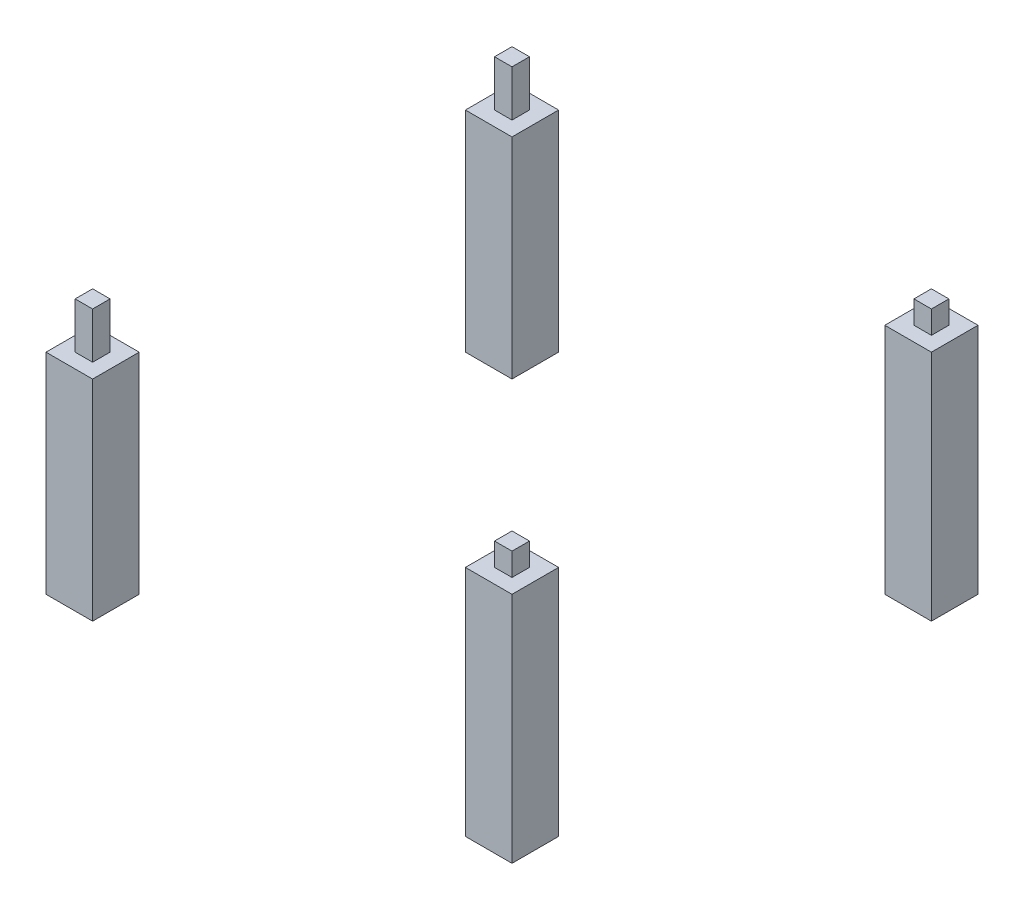
SolidWorks part; units mm, degrees
ref_plane "Front Plane" through (0, 0, 0) normal (0, 0, 1) x (1, 0, 0)
ref_plane "Top Plane" through (0, 0, 0) normal (0, 1, 0) x (1, 0, 0)
ref_plane "Right Plane" through (0, 0, 0) normal (1, 0, 0) x (0, 0, -1)
sketch "Croquis2" plane through (0, 0, 0) normal (0, 1, 0) x (1, 0, 0)
  line L1 (-90, -90) -> (90, -90) construction
  line L2 (-90, -90) -> (-90, 90) construction
  line L3 (-90, 90) -> (90, 90) construction
  line L4 (90, -90) -> (90, 90) construction
  line L5 (-90, -90) -> (90, 90) construction
  line L6 (-90, 90) -> (90, -90) construction
  line L11 (-86, -94) -> (-94, -86) construction
  line L12 (-86, -86) -> (-94, -94) construction
  line L13 (-100, -100) -> (-80, -100)
  line L14 (-100, -100) -> (-100, -80)
  line L15 (-100, -80) -> (-80, -80)
  line L16 (-80, -100) -> (-80, -80)
  line L17 (-100, -100) -> (-80, -80) construction
  line L18 (-100, -80) -> (-80, -100) construction
  line L19 (80, -100) -> (100, -100)
  line L20 (80, -100) -> (100, -80) construction
  line L21 (80, -80) -> (100, -100) construction
  line L22 (80, -80) -> (100, -80)
  line L24 (100, -100) -> (100, -80)
  line L29 (80, -100) -> (80, -80)
  line L33 (-100, 80) -> (-100, 100)
  line L35 (-80, 80) -> (-80, 100)
  line L36 (-100, 80) -> (-80, 100) construction
  line L37 (-100, 100) -> (-80, 80) construction
  line L40 (-100, 80) -> (-80, 80)
  line L41 (-100, 100) -> (-80, 100)
  line L43 (80, 100) -> (100, 80) construction
  line L44 (100, 80) -> (100, 100)
  line L45 (80, 80) -> (80, 100)
  line L48 (80, 80) -> (100, 100) construction
  line L49 (80, 100) -> (100, 100)
  line L51 (80, 80) -> (100, 80)
  point P0 (0, 0)
  point P14 (0, 0)
  point P38 (0, 0)
  point P39 (0, 0)
  point P40 (0, 0)
  dimension "D1" = 180
  dimension "D2" = 180
  dimension "D3" = 20
extrude "Saliente-Extruir3" add sketch "Croquis2" along normal blind 90 contours L13 L16 L15 L14 | L35 L41 L33 L40
sketch "Croquis5" plane through (0, 0, 0) normal (0, 1, 0) x (1, 0, 0)
  line L1 (80, -100) -> (100, -100)
  line L2 (80, -100) -> (80, -80)
  line L3 (80, -80) -> (100, -80)
  line L4 (100, -100) -> (100, -80)
  line L5 (80, -100) -> (100, -80) construction
  line L6 (80, -80) -> (100, -100) construction
  line L7 (80, 80) -> (100, 80)
  line L8 (80, 80) -> (80, 100)
  line L9 (80, 100) -> (100, 100)
  line L10 (100, 80) -> (100, 100)
  line L11 (80, 80) -> (100, 100) construction
  line L12 (80, 100) -> (100, 80) construction
  point P1 (90, -90)
  point P7 (90, 90)
extrude "Saliente-Extruir4" add sketch "Croquis5" along normal blind 100 separate body
sketch "Croquis6" plane through (0, 100, 0) normal (0, 1, 0) x (1, 0, 0)
  line L0 (80, -100) -> (100, -80) construction
  line L1 (86.25, -93.75) -> (93.75, -93.75)
  line L2 (86.25, -93.75) -> (86.25, -86.25)
  line L3 (86.25, -86.25) -> (93.75, -86.25)
  line L4 (93.75, -93.75) -> (93.75, -86.25)
  line L5 (86.25, -93.75) -> (93.75, -86.25) construction
  line L6 (86.25, -86.25) -> (93.75, -93.75) construction
  line L7 (80, 80) -> (100, 100) construction
  line L8 (86.25, 86.25) -> (93.75, 86.25)
  line L9 (86.25, 86.25) -> (86.25, 93.75)
  line L10 (86.25, 93.75) -> (93.75, 93.75)
  line L11 (93.75, 86.25) -> (93.75, 93.75)
  line L12 (86.25, 86.25) -> (93.75, 93.75) construction
  line L13 (86.25, 93.75) -> (93.75, 86.25) construction
  point P0 (90, -90)
  point P7 (90, 90)
  dimension "D1" = 7.5
  dimension "D2" = 7.5
extrude "Saliente-Extruir5" add sketch "Croquis6" along normal blind 9.8
sketch "Croquis7" plane through (0, 90, 0) normal (0, 1, 0) x (1, 0, 0)
  line L0 (-100, 80) -> (-80, 100) construction
  line L1 (-93.75, -93.75) -> (-86.25, -93.75)
  line L2 (-93.75, -93.75) -> (-93.75, -86.25)
  line L3 (-93.75, -86.25) -> (-86.25, -86.25)
  line L4 (-86.25, -93.75) -> (-86.25, -86.25)
  line L5 (-93.75, -93.75) -> (-86.25, -86.25) construction
  line L6 (-93.75, -86.25) -> (-86.25, -93.75) construction
  line L7 (-93.75, 86.25) -> (-86.25, 86.25)
  line L8 (-93.75, 86.25) -> (-93.75, 93.75)
  line L9 (-93.75, 93.75) -> (-86.25, 93.75)
  line L10 (-86.25, 86.25) -> (-86.25, 93.75)
  line L11 (-93.75, 86.25) -> (-86.25, 93.75) construction
  line L12 (-93.75, 93.75) -> (-86.25, 86.25) construction
  point P0 (-90, -90)
  point P7 (-90, 90)
  point P15 (0, 0)
  dimension "D1" = 7.5
  dimension "D2" = 7.5
extrude "Saliente-Extruir6" add sketch "Croquis7" along normal blind 19.8
